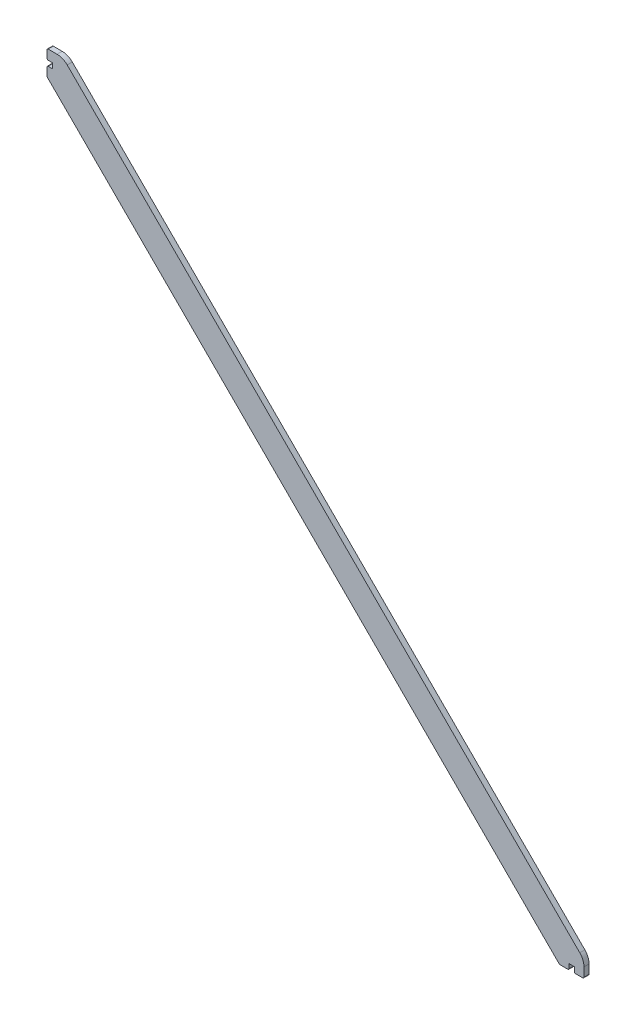
SolidWorks part; units mm, degrees
ref_plane "Front Plane" through (0, 0, 0) normal (0, 0, 1) x (1, 0, 0)
ref_plane "Top Plane" through (0, 0, 0) normal (0, 1, 0) x (1, 0, 0)
ref_plane "Right Plane" through (0, 0, 0) normal (1, 0, 0) x (0, 0, -1)
sketch "Sketch1" plane through (0, 0, 0) normal (0, 0, 1) x (1, 0, 0)
  line L0 (-209.305, 193.395) -> (197.045, -212.955) construction
  line L1 (-205, -205) -> (205, -205) construction
  line L2 (-205, -205) -> (-205, 205) construction
  line L3 (-205, 205) -> (205, 205) construction
  line L4 (205, -205) -> (205, 205) construction
  line L5 (-205, -205) -> (205, 205) construction
  line L6 (-205, 205) -> (205, -205) construction
  line L7 (-197.045, 212.955) -> (212.955, -197.045) construction
  line L8 (-205, 212.6) -> (205, 212.6) construction
  line L9 (-205, 205) -> (-235.5198, 205) construction
  line L10 (-205, 200.9) -> (-235.5198, 200.9) construction
  line L11 (-201.35, 212.6) -> (-208.305, 212.6)
  line L12 (-209.305, 211.6) -> (-209.305, 206)
  line L13 (-208.305, 205) -> (-205, 205)
  line L14 (-205, 205) -> (-205, 200.9)
  line L15 (-205, 200.9) -> (-208.305, 200.9)
  line L16 (-201.35, 201.35) -> (-201.35, 237.7328) construction
  line L17 (-209.305, 193.395) -> (-209.305, 237.7328) construction
  line L18 (-212.955, 197.045) -> (197.045, -212.955) construction
  line L19 (-209.305, 199.9) -> (-209.305, 193.8093)
  line L20 (-209.0121, 193.1022) -> (-205, 189.0901)
  line L21 (-193.395, 209.305) -> (-189.0901, 205)
  line L22 (209.305, -193.395) -> (205, -189.0901)
  line L23 (193.1022, -209.0121) -> (189.0901, -205)
  line L24 (199.9, -209.305) -> (193.8093, -209.305)
  line L25 (200.9, -205) -> (200.9, -208.305)
  line L26 (205, -205) -> (200.9, -205)
  line L27 (205, -208.305) -> (205, -205)
  line L28 (211.6, -209.305) -> (206, -209.305)
  line L29 (212.6, -201.35) -> (212.6, -208.305)
  line L30 (-189.0901, 205) -> (205, -189.0901)
  line L31 (-205, 189.0901) -> (189.0901, -205)
  circle A0 centre (-201.35, 201.35) radius 11.25 construction
  arc A1 (-193.395, 209.305) -> (-201.35, 212.6) centre (-201.35, 201.35) ccw
  arc A2 (-208.305, 212.6) -> (-209.305, 211.6) centre (-208.305, 211.6) ccw
  arc A3 (-208.305, 200.9) -> (-209.305, 199.9) centre (-208.305, 199.9) ccw
  arc A4 (-209.305, 206) -> (-208.305, 205) centre (-208.305, 206) ccw
  arc A5 (-209.305, 193.8093) -> (-209.0121, 193.1022) centre (-208.305, 193.8093) ccw
  circle A6 centre (201.35, -201.35) radius 11.25 construction
  arc A7 (193.8093, -209.305) -> (193.1022, -209.0121) centre (193.8093, -208.305) cw
  arc A8 (206, -209.305) -> (205, -208.305) centre (206, -208.305) cw
  arc A9 (200.9, -208.305) -> (199.9, -209.305) centre (199.9, -208.305) cw
  arc A10 (212.6, -208.305) -> (211.6, -209.305) centre (211.6, -208.305) cw
  arc A11 (209.305, -193.395) -> (212.6, -201.35) centre (201.35, -201.35) cw
  point P0 (0, 0)
  point P30 (-209.305, 200.9)
  point P33 (-209.305, 205)
  point P57 (205, -209.305)
  point P58 (200.9, -209.305)
  dimension "D7" = 1
  dimension "D8" = 1
  dimension "SIZE" = 410
  dimension "D2" = 11.25
  dimension "D6" = 4.305
  dimension "D3" = 11.25
  dimension "D4" = 7.6
  dimension "D5" = 4.1
extrude "Boss-Extrude1" add sketch "Sketch1" along normal blind 4
